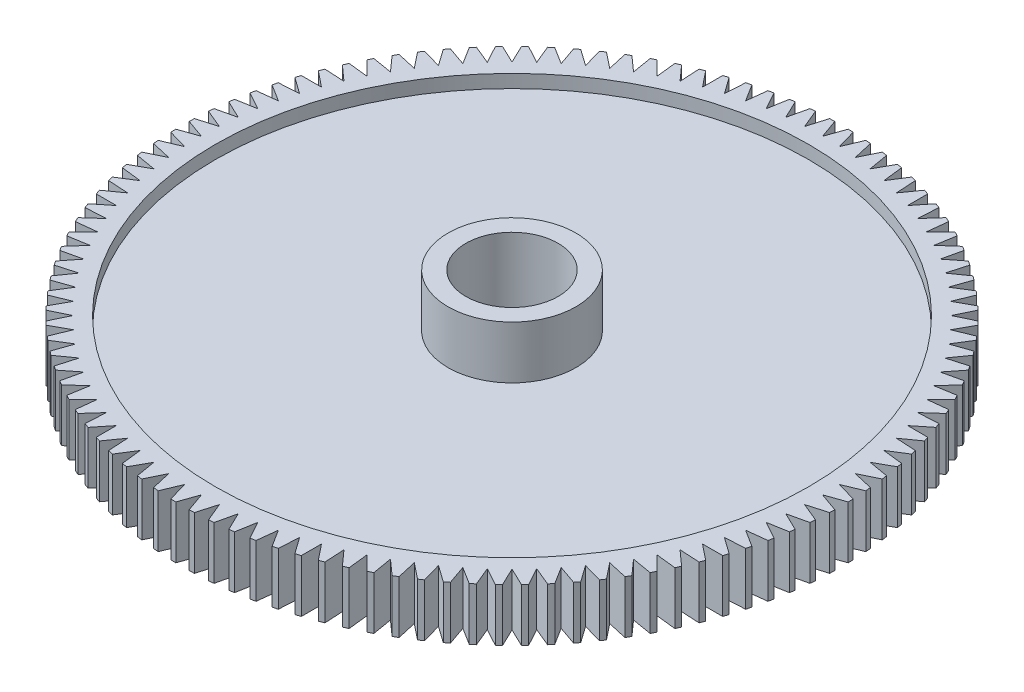
SolidWorks part; units mm, degrees
ref_plane "Спереди" through (0, 0, 0) normal (0, 0, 1) x (1, 0, 0)
ref_plane "Сверху" through (0, 0, 0) normal (0, 1, 0) x (1, 0, 0)
ref_plane "Справа" through (0, 0, 0) normal (1, 0, 0) x (0, 0, -1)
sketch "Эскиз1" plane through (0, 0, 0) normal (0, 1, 0) x (1, 0, 0)
  circle A1 centre (0, 0) radius 25
extrude "Вытянуть1" add sketch "Эскиз1" along normal blind 4
sketch "Эскиз3" plane through (0, 4, 0) normal (0, 1, 0) x (1, 0, 0)
  circle A0 centre (0, 0) radius 3.5
extrude "Вытянуть4" cut sketch "Эскиз3" against normal through all
sketch "Эскиз5" plane through (0, 0, 0) normal (0, 1, 0) x (1, 0, 0)
  line L0 (-0.6185, 25.3105) -> (0.6185, 25.3105)
  line L1 (-0.6185, 25.3105) -> (0, 23.5517)
  line L2 (0, 23.5517) -> (0.6185, 25.3105)
  line L3 (0, 0) -> (0, 15.2434) construction
  line L4 (0.8017, 25.3053) -> (1.3206, 23.5147)
  line L5 (1.3206, 23.5147) -> (2.0367, 25.236)
  line L6 (0.8017, 25.3053) -> (2.0367, 25.236)
  line L7 (2.2193, 25.2206) -> (2.637, 23.4036)
  line L8 (2.637, 23.4036) -> (3.4485, 25.0821)
  line L9 (2.2193, 25.2206) -> (3.4485, 25.0821)
  line L10 (3.6299, 25.0565) -> (3.9451, 23.2189)
  line L11 (3.9451, 23.2189) -> (4.8494, 24.8493)
  line L12 (3.6299, 25.0565) -> (4.8494, 24.8493)
  line L13 (5.0291, 24.8135) -> (5.2407, 22.9612)
  line L14 (5.2407, 22.9612) -> (6.2351, 24.5383)
  line L15 (5.0291, 24.8135) -> (6.2351, 24.5383)
  line L16 (6.4125, 24.4925) -> (6.5199, 22.6312)
  line L17 (6.5199, 22.6312) -> (7.6011, 24.15)
  line L18 (6.4125, 24.4925) -> (7.6011, 24.15)
  line L19 (7.7757, 24.0944) -> (7.7786, 22.2301)
  line L20 (7.7786, 22.2301) -> (8.9433, 23.6859)
  line L21 (7.7757, 24.0944) -> (8.9433, 23.6859)
  line L22 (9.1145, 23.6205) -> (9.0128, 21.7589)
  line L23 (9.0128, 21.7589) -> (10.2573, 23.1471)
  line L24 (9.1145, 23.6205) -> (10.2573, 23.1471)
  line L25 (10.4246, 23.0723) -> (10.2187, 21.2194)
  line L26 (10.2187, 21.2194) -> (11.539, 22.5356)
  line L27 (10.4246, 23.0723) -> (11.539, 22.5356)
  line L28 (11.7018, 22.4515) -> (11.3924, 20.613)
  line L29 (11.3924, 20.613) -> (12.7845, 21.8531)
  line L30 (11.7018, 22.4515) -> (12.7845, 21.8531)
  line L31 (12.9423, 21.76) -> (12.5303, 19.9418)
  line L32 (12.5303, 19.9418) -> (13.9897, 21.1019)
  line L33 (12.9423, 21.76) -> (13.9897, 21.1019)
  line L34 (14.142, 21.0001) -> (13.6287, 19.2079)
  line L35 (13.6287, 19.2079) -> (15.1508, 20.2843)
  line L36 (14.142, 21.0001) -> (15.1508, 20.2843)
  line L37 (15.2973, 20.1741) -> (14.6843, 18.4135)
  line L38 (14.6843, 18.4135) -> (16.2644, 19.4029)
  line L39 (15.2973, 20.1741) -> (16.2644, 19.4029)
  line L40 (16.4044, 19.2847) -> (15.6936, 17.5611)
  line L41 (15.6936, 17.5611) -> (17.3267, 18.4604)
  line L42 (16.4044, 19.2847) -> (17.3267, 18.4604)
  line L43 (17.4599, 18.3345) -> (16.6536, 16.6536)
  line L44 (16.6536, 16.6536) -> (18.3345, 17.4599)
  line L45 (17.4599, 18.3345) -> (18.3345, 17.4599)
  line L46 (18.4604, 17.3267) -> (17.5611, 15.6936)
  line L47 (17.5611, 15.6936) -> (19.2847, 16.4044)
  line L48 (18.4604, 17.3267) -> (19.2847, 16.4044)
  line L49 (19.4029, 16.2644) -> (18.4135, 14.6843)
  line L50 (18.4135, 14.6843) -> (20.1741, 15.2973)
  line L51 (19.4029, 16.2644) -> (20.1741, 15.2973)
  line L52 (20.2843, 15.1508) -> (19.2079, 13.6287)
  line L53 (19.2079, 13.6287) -> (21.0001, 14.142)
  line L54 (20.2843, 15.1508) -> (21.0001, 14.142)
  line L55 (21.1019, 13.9897) -> (19.9418, 12.5303)
  line L56 (19.9418, 12.5303) -> (21.76, 12.9423)
  line L57 (21.1019, 13.9897) -> (21.76, 12.9423)
  line L58 (21.8531, 12.7845) -> (20.613, 11.3924)
  line L59 (20.613, 11.3924) -> (22.4515, 11.7018)
  line L60 (21.8531, 12.7845) -> (22.4515, 11.7018)
  line L61 (22.5356, 11.539) -> (21.2194, 10.2187)
  line L62 (21.2194, 10.2187) -> (23.0723, 10.4246)
  line L63 (22.5356, 11.539) -> (23.0723, 10.4246)
  line L64 (23.1471, 10.2573) -> (21.7589, 9.0128)
  line L65 (21.7589, 9.0128) -> (23.6205, 9.1145)
  line L66 (23.1471, 10.2573) -> (23.6205, 9.1145)
  line L67 (23.6859, 8.9433) -> (22.2301, 7.7786)
  line L68 (22.2301, 7.7786) -> (24.0944, 7.7757)
  line L69 (23.6859, 8.9433) -> (24.0944, 7.7757)
  line L70 (24.15, 7.6011) -> (22.6312, 6.5199)
  line L71 (22.6312, 6.5199) -> (24.4925, 6.4125)
  line L72 (24.15, 7.6011) -> (24.4925, 6.4125)
  line L73 (24.5383, 6.2351) -> (22.9612, 5.2407)
  line L74 (22.9612, 5.2407) -> (24.8135, 5.0291)
  line L75 (24.5383, 6.2351) -> (24.8135, 5.0291)
  line L76 (24.8493, 4.8494) -> (23.2189, 3.9451)
  line L77 (23.2189, 3.9451) -> (25.0565, 3.6299)
  line L78 (24.8493, 4.8494) -> (25.0565, 3.6299)
  line L79 (25.0821, 3.4485) -> (23.4036, 2.637)
  line L80 (23.4036, 2.637) -> (25.2206, 2.2193)
  line L81 (25.0821, 3.4485) -> (25.2206, 2.2193)
  line L82 (25.236, 2.0367) -> (23.5147, 1.3206)
  line L83 (23.5147, 1.3206) -> (25.3053, 0.8017)
  line L84 (25.236, 2.0367) -> (25.3053, 0.8017)
  line L85 (25.3105, 0.6185) -> (23.5517, 0)
  line L86 (23.5517, 0) -> (25.3105, -0.6185)
  line L87 (25.3105, 0.6185) -> (25.3105, -0.6185)
  line L88 (25.3053, -0.8017) -> (23.5147, -1.3206)
  line L89 (23.5147, -1.3206) -> (25.236, -2.0367)
  line L90 (25.3053, -0.8017) -> (25.236, -2.0367)
  line L91 (25.2206, -2.2193) -> (23.4036, -2.637)
  line L92 (23.4036, -2.637) -> (25.0821, -3.4485)
  line L93 (25.2206, -2.2193) -> (25.0821, -3.4485)
  line L94 (25.0565, -3.6299) -> (23.2189, -3.9451)
  line L95 (23.2189, -3.9451) -> (24.8493, -4.8494)
  line L96 (25.0565, -3.6299) -> (24.8493, -4.8494)
  line L97 (24.8135, -5.0291) -> (22.9612, -5.2407)
  line L98 (22.9612, -5.2407) -> (24.5383, -6.2351)
  line L99 (24.8135, -5.0291) -> (24.5383, -6.2351)
  line L100 (24.4925, -6.4125) -> (22.6312, -6.5199)
  line L101 (22.6312, -6.5199) -> (24.15, -7.6011)
  line L102 (24.4925, -6.4125) -> (24.15, -7.6011)
  line L103 (24.0944, -7.7757) -> (22.2301, -7.7786)
  line L104 (22.2301, -7.7786) -> (23.6859, -8.9433)
  line L105 (24.0944, -7.7757) -> (23.6859, -8.9433)
  line L106 (23.6205, -9.1145) -> (21.7589, -9.0128)
  line L107 (21.7589, -9.0128) -> (23.1471, -10.2573)
  line L108 (23.6205, -9.1145) -> (23.1471, -10.2573)
  line L109 (23.0723, -10.4246) -> (21.2194, -10.2187)
  line L110 (21.2194, -10.2187) -> (22.5356, -11.539)
  line L111 (23.0723, -10.4246) -> (22.5356, -11.539)
  line L112 (22.4515, -11.7018) -> (20.613, -11.3924)
  line L113 (20.613, -11.3924) -> (21.8531, -12.7845)
  line L114 (22.4515, -11.7018) -> (21.8531, -12.7845)
  line L115 (21.76, -12.9423) -> (19.9418, -12.5303)
  line L116 (19.9418, -12.5303) -> (21.1019, -13.9897)
  line L117 (21.76, -12.9423) -> (21.1019, -13.9897)
  line L118 (21.0001, -14.142) -> (19.2079, -13.6287)
  line L119 (19.2079, -13.6287) -> (20.2843, -15.1508)
  line L120 (21.0001, -14.142) -> (20.2843, -15.1508)
  line L121 (20.1741, -15.2973) -> (18.4135, -14.6843)
  line L122 (18.4135, -14.6843) -> (19.4029, -16.2644)
  line L123 (20.1741, -15.2973) -> (19.4029, -16.2644)
  line L124 (19.2847, -16.4044) -> (17.5611, -15.6936)
  line L125 (17.5611, -15.6936) -> (18.4604, -17.3267)
  line L126 (19.2847, -16.4044) -> (18.4604, -17.3267)
  line L127 (18.3345, -17.4599) -> (16.6536, -16.6536)
  line L128 (16.6536, -16.6536) -> (17.4599, -18.3345)
  line L129 (18.3345, -17.4599) -> (17.4599, -18.3345)
  line L130 (17.3267, -18.4604) -> (15.6936, -17.5611)
  line L131 (15.6936, -17.5611) -> (16.4044, -19.2847)
  line L132 (17.3267, -18.4604) -> (16.4044, -19.2847)
  line L133 (16.2644, -19.4029) -> (14.6843, -18.4135)
  line L134 (14.6843, -18.4135) -> (15.2973, -20.1741)
  line L135 (16.2644, -19.4029) -> (15.2973, -20.1741)
  line L136 (15.1508, -20.2843) -> (13.6287, -19.2079)
  line L137 (13.6287, -19.2079) -> (14.142, -21.0001)
  line L138 (15.1508, -20.2843) -> (14.142, -21.0001)
  line L139 (13.9897, -21.1019) -> (12.5303, -19.9418)
  line L140 (12.5303, -19.9418) -> (12.9423, -21.76)
  line L141 (13.9897, -21.1019) -> (12.9423, -21.76)
  line L142 (12.7845, -21.8531) -> (11.3924, -20.613)
  line L143 (11.3924, -20.613) -> (11.7018, -22.4515)
  line L144 (12.7845, -21.8531) -> (11.7018, -22.4515)
  line L145 (11.539, -22.5356) -> (10.2187, -21.2194)
  line L146 (10.2187, -21.2194) -> (10.4246, -23.0723)
  line L147 (11.539, -22.5356) -> (10.4246, -23.0723)
  line L148 (10.2573, -23.1471) -> (9.0128, -21.7589)
  line L149 (9.0128, -21.7589) -> (9.1145, -23.6205)
  line L150 (10.2573, -23.1471) -> (9.1145, -23.6205)
  line L151 (8.9433, -23.6859) -> (7.7786, -22.2301)
  line L152 (7.7786, -22.2301) -> (7.7757, -24.0944)
  line L153 (8.9433, -23.6859) -> (7.7757, -24.0944)
  line L154 (7.6011, -24.15) -> (6.5199, -22.6312)
  line L155 (6.5199, -22.6312) -> (6.4125, -24.4925)
  line L156 (7.6011, -24.15) -> (6.4125, -24.4925)
  line L157 (6.2351, -24.5383) -> (5.2407, -22.9612)
  line L158 (5.2407, -22.9612) -> (5.0291, -24.8135)
  line L159 (6.2351, -24.5383) -> (5.0291, -24.8135)
  line L160 (4.8494, -24.8493) -> (3.9451, -23.2189)
  line L161 (3.9451, -23.2189) -> (3.6299, -25.0565)
  line L162 (4.8494, -24.8493) -> (3.6299, -25.0565)
  line L163 (3.4485, -25.0821) -> (2.637, -23.4036)
  line L164 (2.637, -23.4036) -> (2.2193, -25.2206)
  line L165 (3.4485, -25.0821) -> (2.2193, -25.2206)
  line L166 (2.0367, -25.236) -> (1.3206, -23.5147)
  line L167 (1.3206, -23.5147) -> (0.8017, -25.3053)
  line L168 (2.0367, -25.236) -> (0.8017, -25.3053)
  line L169 (0.6185, -25.3105) -> (0, -23.5517)
  line L170 (0, -23.5517) -> (-0.6185, -25.3105)
  line L171 (0.6185, -25.3105) -> (-0.6185, -25.3105)
  line L172 (-0.8017, -25.3053) -> (-1.3206, -23.5147)
  line L173 (-1.3206, -23.5147) -> (-2.0367, -25.236)
  line L174 (-0.8017, -25.3053) -> (-2.0367, -25.236)
  line L175 (-2.2193, -25.2206) -> (-2.637, -23.4036)
  line L176 (-2.637, -23.4036) -> (-3.4485, -25.0821)
  line L177 (-2.2193, -25.2206) -> (-3.4485, -25.0821)
  line L178 (-3.6299, -25.0565) -> (-3.9451, -23.2189)
  line L179 (-3.9451, -23.2189) -> (-4.8494, -24.8493)
  line L180 (-3.6299, -25.0565) -> (-4.8494, -24.8493)
  line L181 (-5.0291, -24.8135) -> (-5.2407, -22.9612)
  line L182 (-5.2407, -22.9612) -> (-6.2351, -24.5383)
  line L183 (-5.0291, -24.8135) -> (-6.2351, -24.5383)
  line L184 (-6.4125, -24.4925) -> (-6.5199, -22.6312)
  line L185 (-6.5199, -22.6312) -> (-7.6011, -24.15)
  line L186 (-6.4125, -24.4925) -> (-7.6011, -24.15)
  line L187 (-7.7757, -24.0944) -> (-7.7786, -22.2301)
  line L188 (-7.7786, -22.2301) -> (-8.9433, -23.6859)
  line L189 (-7.7757, -24.0944) -> (-8.9433, -23.6859)
  line L190 (-9.1145, -23.6205) -> (-9.0128, -21.7589)
  line L191 (-9.0128, -21.7589) -> (-10.2573, -23.1471)
  line L192 (-9.1145, -23.6205) -> (-10.2573, -23.1471)
  line L193 (-10.4246, -23.0723) -> (-10.2187, -21.2194)
  line L194 (-10.2187, -21.2194) -> (-11.539, -22.5356)
  line L195 (-10.4246, -23.0723) -> (-11.539, -22.5356)
  line L196 (-11.7018, -22.4515) -> (-11.3924, -20.613)
  line L197 (-11.3924, -20.613) -> (-12.7845, -21.8531)
  line L198 (-11.7018, -22.4515) -> (-12.7845, -21.8531)
  line L199 (-12.9423, -21.76) -> (-12.5303, -19.9418)
  line L200 (-12.5303, -19.9418) -> (-13.9897, -21.1019)
  line L201 (-12.9423, -21.76) -> (-13.9897, -21.1019)
  line L202 (-14.142, -21.0001) -> (-13.6287, -19.2079)
  line L203 (-13.6287, -19.2079) -> (-15.1508, -20.2843)
  line L204 (-14.142, -21.0001) -> (-15.1508, -20.2843)
  line L205 (-15.2973, -20.1741) -> (-14.6843, -18.4135)
  line L206 (-14.6843, -18.4135) -> (-16.2644, -19.4029)
  line L207 (-15.2973, -20.1741) -> (-16.2644, -19.4029)
  line L208 (-16.4044, -19.2847) -> (-15.6936, -17.5611)
  line L209 (-15.6936, -17.5611) -> (-17.3267, -18.4604)
  line L210 (-16.4044, -19.2847) -> (-17.3267, -18.4604)
  line L211 (-17.4599, -18.3345) -> (-16.6536, -16.6536)
  line L212 (-16.6536, -16.6536) -> (-18.3345, -17.4599)
  line L213 (-17.4599, -18.3345) -> (-18.3345, -17.4599)
  line L214 (-18.4604, -17.3267) -> (-17.5611, -15.6936)
  line L215 (-17.5611, -15.6936) -> (-19.2847, -16.4044)
  line L216 (-18.4604, -17.3267) -> (-19.2847, -16.4044)
  line L217 (-19.4029, -16.2644) -> (-18.4135, -14.6843)
  line L218 (-18.4135, -14.6843) -> (-20.1741, -15.2973)
  line L219 (-19.4029, -16.2644) -> (-20.1741, -15.2973)
  line L220 (-20.2843, -15.1508) -> (-19.2079, -13.6287)
  line L221 (-19.2079, -13.6287) -> (-21.0001, -14.142)
  line L222 (-20.2843, -15.1508) -> (-21.0001, -14.142)
  line L223 (-21.1019, -13.9897) -> (-19.9418, -12.5303)
  line L224 (-19.9418, -12.5303) -> (-21.76, -12.9423)
  line L225 (-21.1019, -13.9897) -> (-21.76, -12.9423)
  line L226 (-21.8531, -12.7845) -> (-20.613, -11.3924)
  line L227 (-20.613, -11.3924) -> (-22.4515, -11.7018)
  line L228 (-21.8531, -12.7845) -> (-22.4515, -11.7018)
  line L229 (-22.5356, -11.539) -> (-21.2194, -10.2187)
  line L230 (-21.2194, -10.2187) -> (-23.0723, -10.4246)
  line L231 (-22.5356, -11.539) -> (-23.0723, -10.4246)
  line L232 (-23.1471, -10.2573) -> (-21.7589, -9.0128)
  line L233 (-21.7589, -9.0128) -> (-23.6205, -9.1145)
  line L234 (-23.1471, -10.2573) -> (-23.6205, -9.1145)
  line L235 (-23.6859, -8.9433) -> (-22.2301, -7.7786)
  line L236 (-22.2301, -7.7786) -> (-24.0944, -7.7757)
  line L237 (-23.6859, -8.9433) -> (-24.0944, -7.7757)
  line L238 (-24.15, -7.6011) -> (-22.6312, -6.5199)
  line L239 (-22.6312, -6.5199) -> (-24.4925, -6.4125)
  line L240 (-24.15, -7.6011) -> (-24.4925, -6.4125)
  line L241 (-24.5383, -6.2351) -> (-22.9612, -5.2407)
  line L242 (-22.9612, -5.2407) -> (-24.8135, -5.0291)
  line L243 (-24.5383, -6.2351) -> (-24.8135, -5.0291)
  line L244 (-24.8493, -4.8494) -> (-23.2189, -3.9451)
  line L245 (-23.2189, -3.9451) -> (-25.0565, -3.6299)
  line L246 (-24.8493, -4.8494) -> (-25.0565, -3.6299)
  line L247 (-25.0821, -3.4485) -> (-23.4036, -2.637)
  line L248 (-23.4036, -2.637) -> (-25.2206, -2.2193)
  line L249 (-25.0821, -3.4485) -> (-25.2206, -2.2193)
  line L250 (-25.236, -2.0367) -> (-23.5147, -1.3206)
  line L251 (-23.5147, -1.3206) -> (-25.3053, -0.8017)
  line L252 (-25.236, -2.0367) -> (-25.3053, -0.8017)
  line L253 (-25.3105, -0.6185) -> (-23.5517, 0)
  line L254 (-23.5517, 0) -> (-25.3105, 0.6185)
  line L255 (-25.3105, -0.6185) -> (-25.3105, 0.6185)
  line L256 (-25.3053, 0.8017) -> (-23.5147, 1.3206)
  line L257 (-23.5147, 1.3206) -> (-25.236, 2.0367)
  line L258 (-25.3053, 0.8017) -> (-25.236, 2.0367)
  line L259 (-25.2206, 2.2193) -> (-23.4036, 2.637)
  line L260 (-23.4036, 2.637) -> (-25.0821, 3.4485)
  line L261 (-25.2206, 2.2193) -> (-25.0821, 3.4485)
  line L262 (-25.0565, 3.6299) -> (-23.2189, 3.9451)
  line L263 (-23.2189, 3.9451) -> (-24.8493, 4.8494)
  line L264 (-25.0565, 3.6299) -> (-24.8493, 4.8494)
  line L265 (-24.8135, 5.0291) -> (-22.9612, 5.2407)
  line L266 (-22.9612, 5.2407) -> (-24.5383, 6.2351)
  line L267 (-24.8135, 5.0291) -> (-24.5383, 6.2351)
  line L268 (-24.4925, 6.4125) -> (-22.6312, 6.5199)
  line L269 (-22.6312, 6.5199) -> (-24.15, 7.6011)
  line L270 (-24.4925, 6.4125) -> (-24.15, 7.6011)
  line L271 (-24.0944, 7.7757) -> (-22.2301, 7.7786)
  line L272 (-22.2301, 7.7786) -> (-23.6859, 8.9433)
  line L273 (-24.0944, 7.7757) -> (-23.6859, 8.9433)
  line L274 (-23.6205, 9.1145) -> (-21.7589, 9.0128)
  line L275 (-21.7589, 9.0128) -> (-23.1471, 10.2573)
  line L276 (-23.6205, 9.1145) -> (-23.1471, 10.2573)
  line L277 (-23.0723, 10.4246) -> (-21.2194, 10.2187)
  line L278 (-21.2194, 10.2187) -> (-22.5356, 11.539)
  line L279 (-23.0723, 10.4246) -> (-22.5356, 11.539)
  line L280 (-22.4515, 11.7018) -> (-20.613, 11.3924)
  line L281 (-20.613, 11.3924) -> (-21.8531, 12.7845)
  line L282 (-22.4515, 11.7018) -> (-21.8531, 12.7845)
  line L283 (-21.76, 12.9423) -> (-19.9418, 12.5303)
  line L284 (-19.9418, 12.5303) -> (-21.1019, 13.9897)
  line L285 (-21.76, 12.9423) -> (-21.1019, 13.9897)
  line L286 (-21.0001, 14.142) -> (-19.2079, 13.6287)
  line L287 (-19.2079, 13.6287) -> (-20.2843, 15.1508)
  line L288 (-21.0001, 14.142) -> (-20.2843, 15.1508)
  line L289 (-20.1741, 15.2973) -> (-18.4135, 14.6843)
  line L290 (-18.4135, 14.6843) -> (-19.4029, 16.2644)
  line L291 (-20.1741, 15.2973) -> (-19.4029, 16.2644)
  line L292 (-19.2847, 16.4044) -> (-17.5611, 15.6936)
  line L293 (-17.5611, 15.6936) -> (-18.4604, 17.3267)
  line L294 (-19.2847, 16.4044) -> (-18.4604, 17.3267)
  line L295 (-18.3345, 17.4599) -> (-16.6536, 16.6536)
  line L296 (-16.6536, 16.6536) -> (-17.4599, 18.3345)
  line L297 (-18.3345, 17.4599) -> (-17.4599, 18.3345)
  line L298 (-17.3267, 18.4604) -> (-15.6936, 17.5611)
  line L299 (-15.6936, 17.5611) -> (-16.4044, 19.2847)
  line L300 (-17.3267, 18.4604) -> (-16.4044, 19.2847)
  line L301 (-16.2644, 19.4029) -> (-14.6843, 18.4135)
  line L302 (-14.6843, 18.4135) -> (-15.2973, 20.1741)
  line L303 (-16.2644, 19.4029) -> (-15.2973, 20.1741)
  line L304 (-15.1508, 20.2843) -> (-13.6287, 19.2079)
  line L305 (-13.6287, 19.2079) -> (-14.142, 21.0001)
  line L306 (-15.1508, 20.2843) -> (-14.142, 21.0001)
  line L307 (-13.9897, 21.1019) -> (-12.5303, 19.9418)
  line L308 (-12.5303, 19.9418) -> (-12.9423, 21.76)
  line L309 (-13.9897, 21.1019) -> (-12.9423, 21.76)
  line L310 (-12.7845, 21.8531) -> (-11.3924, 20.613)
  line L311 (-11.3924, 20.613) -> (-11.7018, 22.4515)
  line L312 (-12.7845, 21.8531) -> (-11.7018, 22.4515)
  line L313 (-11.539, 22.5356) -> (-10.2187, 21.2194)
  line L314 (-10.2187, 21.2194) -> (-10.4246, 23.0723)
  line L315 (-11.539, 22.5356) -> (-10.4246, 23.0723)
  line L316 (-10.2573, 23.1471) -> (-9.0128, 21.7589)
  line L317 (-9.0128, 21.7589) -> (-9.1145, 23.6205)
  line L318 (-10.2573, 23.1471) -> (-9.1145, 23.6205)
  line L319 (-8.9433, 23.6859) -> (-7.7786, 22.2301)
  line L320 (-7.7786, 22.2301) -> (-7.7757, 24.0944)
  line L321 (-8.9433, 23.6859) -> (-7.7757, 24.0944)
  line L322 (-7.6011, 24.15) -> (-6.5199, 22.6312)
  line L323 (-6.5199, 22.6312) -> (-6.4125, 24.4925)
  line L324 (-7.6011, 24.15) -> (-6.4125, 24.4925)
  line L325 (-6.2351, 24.5383) -> (-5.2407, 22.9612)
  line L326 (-5.2407, 22.9612) -> (-5.0291, 24.8135)
  line L327 (-6.2351, 24.5383) -> (-5.0291, 24.8135)
  line L328 (-4.8494, 24.8493) -> (-3.9451, 23.2189)
  line L329 (-3.9451, 23.2189) -> (-3.6299, 25.0565)
  line L330 (-4.8494, 24.8493) -> (-3.6299, 25.0565)
  line L331 (-3.4485, 25.0821) -> (-2.637, 23.4036)
  line L332 (-2.637, 23.4036) -> (-2.2193, 25.2206)
  line L333 (-3.4485, 25.0821) -> (-2.2193, 25.2206)
  line L334 (-2.0367, 25.236) -> (-1.3206, 23.5147)
  line L335 (-1.3206, 23.5147) -> (-0.8017, 25.3053)
  line L336 (-2.0367, 25.236) -> (-0.8017, 25.3053)
extrude "Вытянуть5" cut sketch "Эскиз5" along normal through all
sketch "Эскиз6" plane through (0, 4, 0) normal (0, 1, 0) x (1, 0, 0)
  circle A0 centre (0, 0) radius 22.5
extrude "Вытянуть6" cut sketch "Эскиз6" against normal blind 1
sketch "Эскиз7" plane through (0, 0, 0) normal (0, -1, 0) x (1, 0, 0)
  circle A0 centre (0, 0) radius 22.5
extrude "Вытянуть7" cut sketch "Эскиз7" against normal blind 1
sketch "Эскиз8" plane through (0, 3, 0) normal (0, 1, 0) x (1, 0, 0)
  circle A0 centre (0, 0) radius 3.5
  circle A1 centre (0, 0) radius 4.85
extrude "Вытянуть8" add sketch "Эскиз8" along normal blind 4
sketch "Эскиз9" plane through (0, 1, 0) normal (0, -1, 0) x (1, 0, 0)
  circle A0 centre (0, 0) radius 3.5
  circle A1 centre (0, 0) radius 7
extrude "Вытянуть9" add sketch "Эскиз9" along normal blind 9
